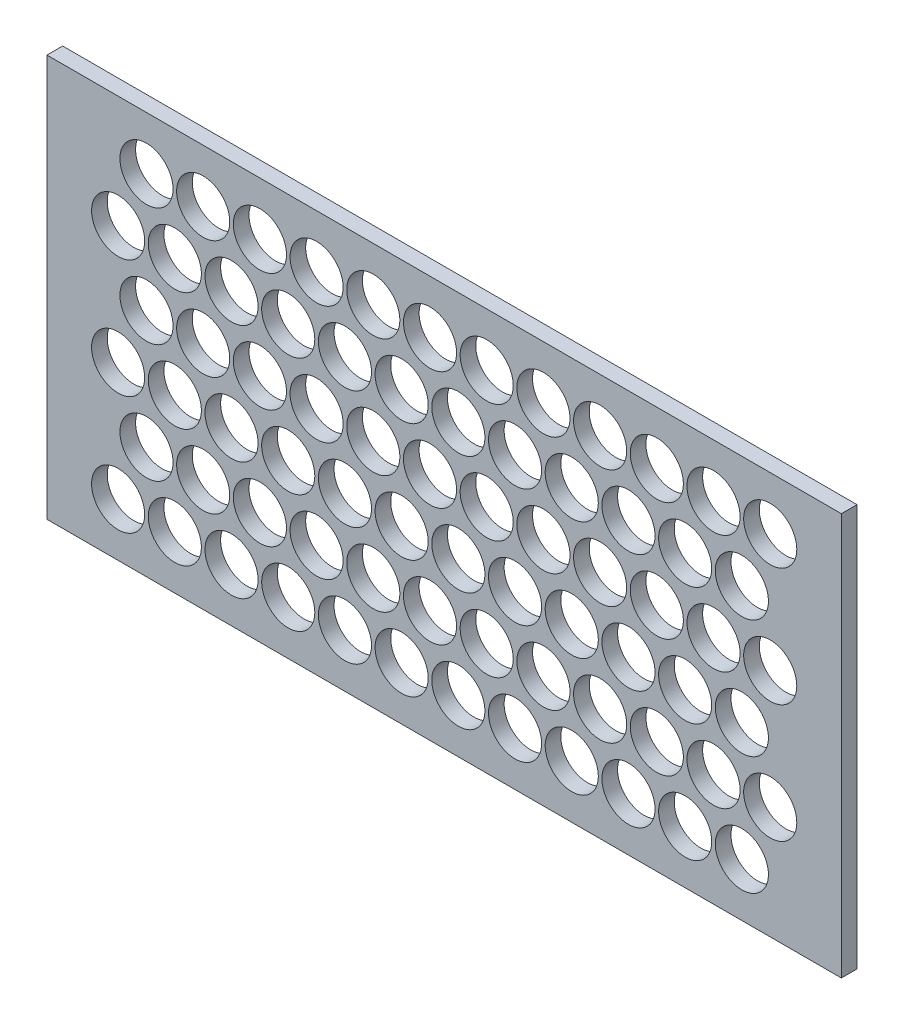
SolidWorks part; units mm, degrees
material "Custom Plastic"
ref_plane "X-Y Datum" through (0, 0, 0) normal (0, 0, 1) x (1, 0, 0)
ref_plane "X-Z Datum" through (0, 0, 0) normal (0, 1, 0) x (1, 0, 0)
ref_plane "Y-Z Datum" through (0, 0, 0) normal (1, 0, 0) x (0, 0, -1)
sketch "Sketch1" plane through (0, 0, 0) normal (0, 0, 1) x (1, 0, 0)
  line L1 (0, 0) -> (322.2286, 0)
  line L2 (0, 0) -> (0, 163.1)
  line L3 (0, 163.1) -> (322.2286, 163.1)
  line L4 (322.2286, 0) -> (322.2286, 163.1)
  dimension "D2" = 163.1
  dimension "D3" = 322.2286
extrude "Boss-Extrude1" add sketch "Sketch1" along normal blind 6.35
sketch "Sketch2" plane through (0, 0, 6.35) normal (0, 0, 1) x (1, 0, 0)
  line L1 (0, 0) -> (322.2286, 0) construction
  line L2 (304.1411, 152.325) -> (304.1411, 163.1)
  line L10 (322.2286, 0) -> (322.2286, 163.1) construction
  line L11 (0, 163.1) -> (322.2286, 163.1) construction
  line L12 (18.0875, 21.55) -> (28.8625, 21.55)
  line L13 (28.8625, 21.55) -> (28.8625, 10.775)
  line L14 (28.8625, 21.55) -> (51.8625, 21.55) construction
  line L15 (28.8625, 21.55) -> (40.3661, 45.545)
  line L16 (40.3661, 45.545) -> (63.3661, 45.545) construction
  line L18 (18.0875, 10.775) -> (304.1411, 10.775)
  line L19 (0, 0) -> (0, 163.1) construction
  line L20 (18.0875, 10.775) -> (18.0875, 152.325)
  line L21 (18.0875, 152.325) -> (304.1411, 152.325)
  line L22 (304.1411, 10.775) -> (304.1411, 152.325)
  circle A0 centre (28.8625, 21.55) radius 10.775
  circle A12 centre (51.8625, 21.55) radius 10.775
  circle A13 centre (74.8625, 21.55) radius 10.775
  circle A14 centre (97.8625, 21.55) radius 10.775
  circle A15 centre (120.8625, 21.55) radius 10.775
  circle A16 centre (143.8625, 21.55) radius 10.775
  circle A17 centre (166.8625, 21.55) radius 10.775
  circle A18 centre (189.8625, 21.55) radius 10.775
  circle A19 centre (212.8625, 21.55) radius 10.775
  circle A20 centre (235.8625, 21.55) radius 10.775
  circle A21 centre (258.8625, 21.55) radius 10.775
  circle A22 centre (281.8625, 21.55) radius 10.775
  circle A23 centre (40.3661, 45.545) radius 10.775
  circle A24 centre (63.3661, 45.545) radius 10.775
  circle A25 centre (86.3661, 45.545) radius 10.775
  circle A26 centre (109.3661, 45.545) radius 10.775
  circle A27 centre (132.3661, 45.545) radius 10.775
  circle A28 centre (155.3661, 45.545) radius 10.775
  circle A29 centre (178.3661, 45.545) radius 10.775
  circle A30 centre (201.3661, 45.545) radius 10.775
  circle A31 centre (224.3661, 45.545) radius 10.775
  circle A32 centre (247.3661, 45.545) radius 10.775
  circle A33 centre (270.3661, 45.545) radius 10.775
  circle A34 centre (293.3661, 45.545) radius 10.775
  circle A35 centre (28.8625, 69.55) radius 10.775
  circle A36 centre (51.8625, 69.55) radius 10.775
  circle A37 centre (74.8625, 69.55) radius 10.775
  circle A38 centre (97.8625, 69.55) radius 10.775
  circle A39 centre (120.8625, 69.55) radius 10.775
  circle A40 centre (143.8625, 69.55) radius 10.775
  circle A41 centre (166.8625, 69.55) radius 10.775
  circle A42 centre (189.8625, 69.55) radius 10.775
  circle A43 centre (212.8625, 69.55) radius 10.775
  circle A44 centre (235.8625, 69.55) radius 10.775
  circle A45 centre (258.8625, 69.55) radius 10.775
  circle A46 centre (281.8625, 69.55) radius 10.775
  circle A47 centre (28.8625, 117.55) radius 10.775
  circle A48 centre (51.8625, 117.55) radius 10.775
  circle A49 centre (74.8625, 117.55) radius 10.775
  circle A50 centre (97.8625, 117.55) radius 10.775
  circle A51 centre (120.8625, 117.55) radius 10.775
  circle A52 centre (143.8625, 117.55) radius 10.775
  circle A53 centre (166.8625, 117.55) radius 10.775
  circle A54 centre (189.8625, 117.55) radius 10.775
  circle A55 centre (212.8625, 117.55) radius 10.775
  circle A56 centre (235.8625, 117.55) radius 10.775
  circle A57 centre (258.8625, 117.55) radius 10.775
  circle A58 centre (281.8625, 117.55) radius 10.775
  circle A59 centre (40.3661, 93.545) radius 10.775
  circle A60 centre (63.3661, 93.545) radius 10.775
  circle A61 centre (86.3661, 93.545) radius 10.775
  circle A62 centre (109.3661, 93.545) radius 10.775
  circle A63 centre (132.3661, 93.545) radius 10.775
  circle A64 centre (155.3661, 93.545) radius 10.775
  circle A65 centre (178.3661, 93.545) radius 10.775
  circle A66 centre (201.3661, 93.545) radius 10.775
  circle A67 centre (224.3661, 93.545) radius 10.775
  circle A68 centre (247.3661, 93.545) radius 10.775
  circle A69 centre (270.3661, 93.545) radius 10.775
  circle A70 centre (293.3661, 93.545) radius 10.775
  circle A71 centre (40.3661, 141.545) radius 10.775
  circle A72 centre (63.3661, 141.545) radius 10.775
  circle A73 centre (86.3661, 141.545) radius 10.775
  circle A74 centre (109.3661, 141.545) radius 10.775
  circle A75 centre (132.3661, 141.545) radius 10.775
  circle A76 centre (155.3661, 141.545) radius 10.775
  circle A77 centre (178.3661, 141.545) radius 10.775
  circle A78 centre (201.3661, 141.545) radius 10.775
  circle A79 centre (224.3661, 141.545) radius 10.775
  circle A80 centre (247.3661, 141.545) radius 10.775
  circle A81 centre (270.3661, 141.545) radius 10.775
  circle A82 centre (293.3661, 141.545) radius 10.775
  dimension "D2" = 18.0875
  dimension "D4" = 23
  dimension "D5" = 12
  dimension "D3" = 23
  dimension "D9" = 10.775
  dimension "D10" = 18.0875
  dimension "D11" = 10.775
  dimension "D12" = 10.775
  dimension "D13" = 26.61
  dimension "D14" = 10.775
  dimension "D7" = 12
  dimension "D6" = 3
  dimension "D8" = 3
extrude "Cut-Extrude1" cut sketch "Sketch2" against normal through all
